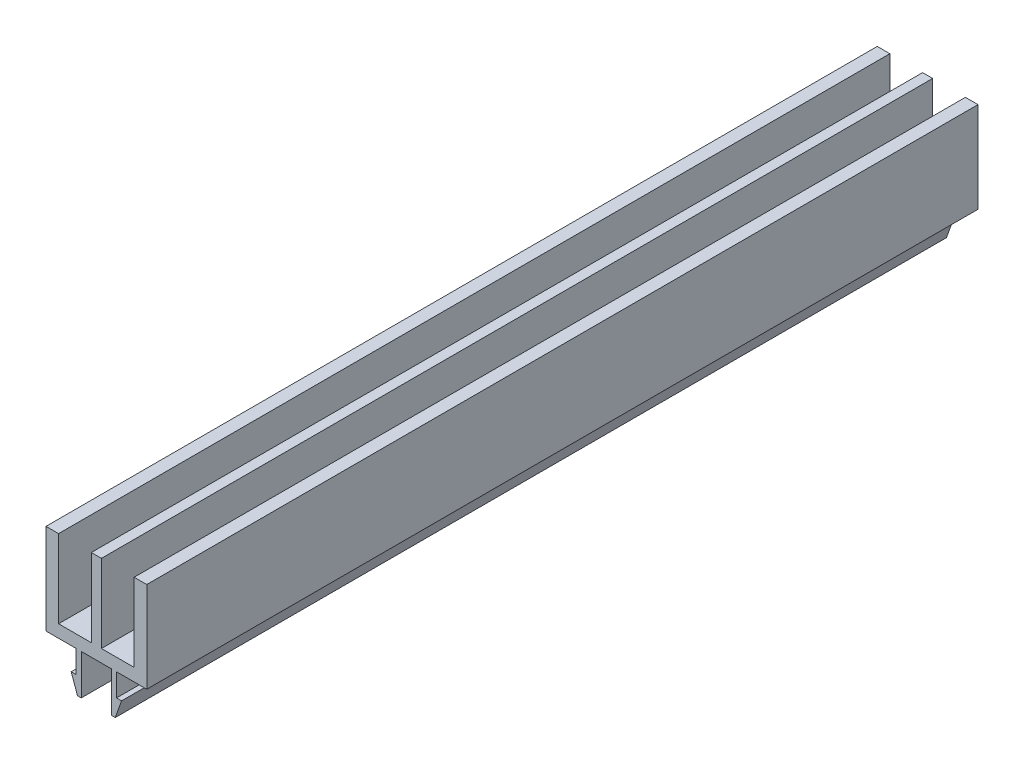
SolidWorks part; units mm, degrees
ref_plane "Plan de face" through (0, 0, 0) normal (0, 0, 1) x (1, 0, 0)
ref_plane "Plan de dessus" through (0, 0, 0) normal (0, 1, 0) x (1, 0, 0)
ref_plane "Plan de droite" through (0, 0, 0) normal (1, 0, 0) x (0, 0, -1)
ref_plane "Plan1" through (0, 0, 50) normal (0, 0, 1) x (1, 0, 0)
sketch "Esquisse1" plane through (0, 0, 50) normal (0, 0, 1) x (1, 0, 0)
  line L0 (-1, 2.5) -> (-7.5, 2.5)
  line L1 (-7.5, 2.5) -> (-7.5, 18)
  line L2 (-7.5, 18) -> (-10, 18)
  line L3 (-10, 18) -> (-10, 0)
  line L4 (-10, 0) -> (-4, 0)
  line L5 (-4, 0) -> (-4, -4.5)
  line L6 (-4, -4.5) -> (-5, -4.5)
  line L7 (-5, -4.5) -> (-3.75, -8)
  line L8 (-3.75, -8) -> (-3, -8)
  line L9 (-3, -8) -> (-3, 0)
  line L10 (-3, 0) -> (3, 0)
  line L11 (3, 0) -> (3, -8)
  line L12 (3, -8) -> (3.75, -8)
  line L13 (3.75, -8) -> (5, -4.5)
  line L14 (5, -4.5) -> (4, -4.5)
  line L15 (4, -4.5) -> (4, 0)
  line L16 (4, 0) -> (10, 0)
  line L17 (10, 0) -> (10, 18)
  line L18 (10, 18) -> (7.5, 18)
  line L19 (7.5, 18) -> (7.5, 2.5)
  line L20 (7.5, 2.5) -> (1, 2.5)
  line L21 (1, 2.5) -> (1, 18)
  line L22 (1, 18) -> (-1, 18)
  line L23 (-1, 18) -> (-1, 2.5)
extrude "Boss.-Extru.1" add sketch "Esquisse1" against normal blind 165
